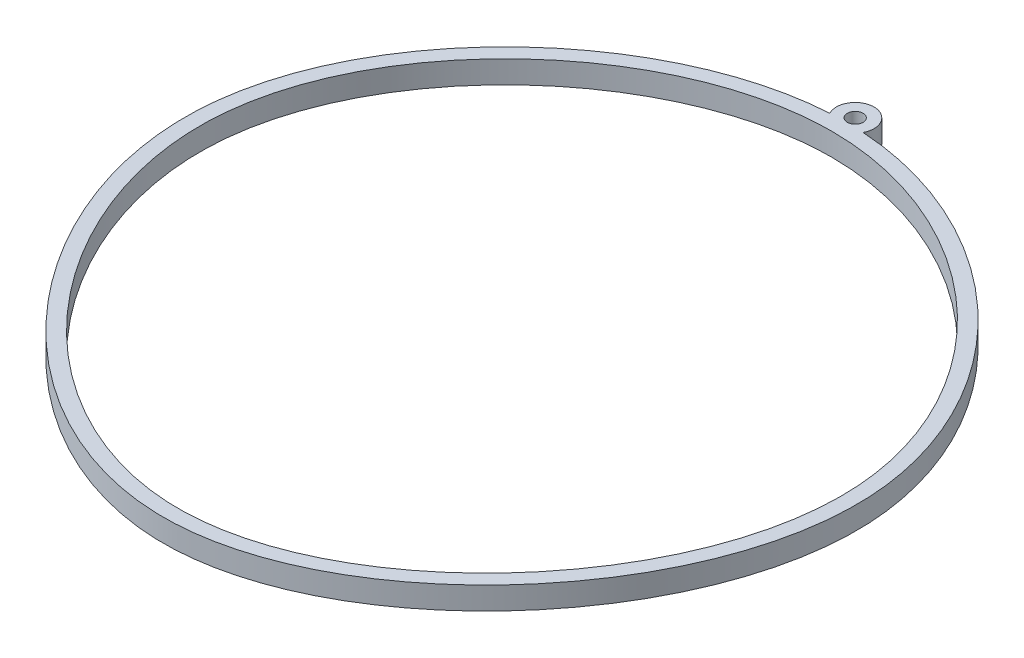
SolidWorks part; units mm, degrees
ref_plane "Front Plane" through (0, 0, 0) normal (0, 0, 1) x (1, 0, 0)
ref_plane "Top Plane" through (0, 0, 0) normal (0, 1, 0) x (1, 0, 0)
ref_plane "Right Plane" through (0, 0, 0) normal (1, 0, 0) x (0, 0, -1)
sketch "Sketch1" plane through (0, 0, 0) normal (0, 1, 0) x (1, 0, 0)
  line L0 (0, 39.087) -> (0, -47.773) construction
  line L1 (-42.5395, 0) -> (42.5395, 0) construction
  line L2 (0, 41.087) -> (0, -49.773) construction
  line L3 (-44.5395, 0) -> (44.5395, 0) construction
  circle A0 centre (0, 42.187) radius 1.05
  arc A1 (2.2105, 41.0192) -> (-2.2105, 41.0192) centre (0, 42.187) ccw
  spline S0 degree 3 poles (-63.9566, -0.0678) (0, 57.6678) (63.9566, -0.0678) (0, -72.8399) (-63.9566, -0.0678) (0, 57.6678) (63.9566, -0.0678) knots -0.762727 -0.5 -0.237273 0 0.237273 0.5 0.762727 1 1.237273 1.5 1.762727 only from (0, 39.087) to (0, 39.087)
  spline S1 degree 3 poles (-66.95, -0.0657) (0, 60.6627) (66.95, -0.0657) (0, -75.8354) (-66.95, -0.0657) (0, 60.6627) (66.95, -0.0657) knots -0.762158 -0.5 -0.237842 0 0.237842 0.5 0.762158 1 1.237842 1.5 1.762158 only from (0, 41.087) to (0, 41.087)
  dimension "D9" = 2.1
  dimension "D10" = 5
  dimension "D1" = 86.86
  dimension "D2" = 85.079
  dimension "D3" = 39.087
  dimension "D4" = 42.5395
  dimension "D5" = 90.86
  dimension "D6" = 2
  dimension "D7" = 89.079
  dimension "D8" = 2
  dimension "D11" = 3.1
extrude "Boss-Extrude1" add sketch "Sketch1" along normal blind 3 contours A1 S1 A0 | S1 S0
equation "\"D7@Sketch1\"=\"D2@Sketch1\"+4"
equation "\"D5@Sketch1\"=\"D1@Sketch1\"+4"
equation "\"D3@Sketch1\"=\"D1@Sketch1\"*0.45"
equation "\"D4@Sketch1\"=\"D2@Sketch1\"*0.5"
